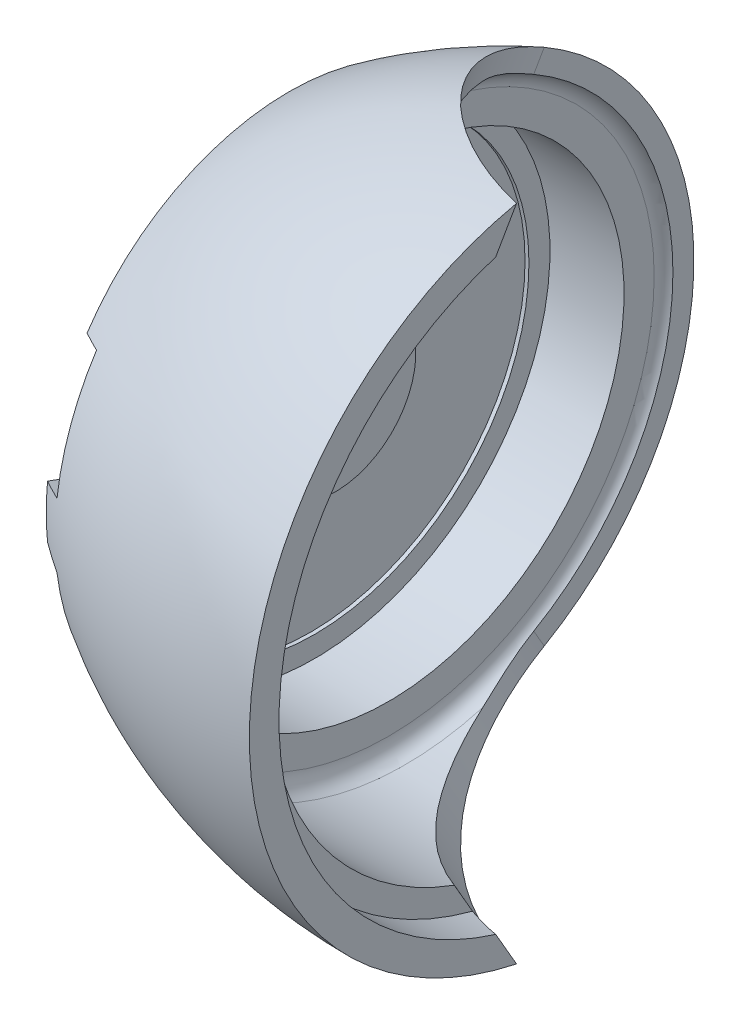
SolidWorks part; units mm, degrees
ref_plane "Front Plane" through (0, 0, 0) normal (0, 0, 1) x (1, 0, 0)
ref_plane "Top Plane" through (0, 0, 0) normal (0, 1, 0) x (1, 0, 0)
ref_plane "Right Plane" through (0, 0, 0) normal (1, 0, 0) x (0, 0, -1)
sketch "Sketch1" plane through (0, 0, 0) normal (0, 0, 1) x (1, 0, 0)
  line L0 (0, -55) -> (0, 55) construction
  line L1 (55, 0) -> (-55, 0) construction
  line L3 (-39.088, 0) -> (-39.088, 12.4)
  line L4 (-39.088, 12.4) -> (-42.39, 12.4)
  line L5 (-42.3, 33.02) -> (-42.3, 36.2585)
  line L7 (-42.988, 0) -> (-39.088, 0)
  line L9 (-30.9, 36.2585) -> (-42.3, 36.2585)
  line L10 (-46.2, 37.409) -> (-46.2, 8.59)
  line L14 (-30.9, 43.434) -> (-5.91, 43.434)
  line L17 (-46.2, 8.59) -> (-42.988, 8.59)
  line L18 (-42.988, 8.59) -> (-42.988, 0)
  line L19 (-42.3, 33.02) -> (-42.9, 33.02)
  line L20 (-42.9, 33.02) -> (-42.9, 12.4)
  line L21 (-42.9, 12.4) -> (-42.39, 12.4)
  line L22 (-30.9, 36.2585) -> (-30.9, 43.434)
  line L23 (-0.51, 51.8144) -> (-0.51, 47.244)
  line L24 (-0.51, 47.244) -> (-5.91, 47.244)
  line L25 (-5.91, 47.244) -> (-5.91, 43.434)
  arc A1 (-0.51, 51.8144) -> (-46.2, 37.409) centre (0, -29.464) ccw
  dimension "D1" = 81.28
  dimension "D2" = 43.434
  dimension "D3" = 46.2
  dimension "D4" = 12.4
  dimension "D5" = 7.112
  dimension "D6" = 11.4
  dimension "D7" = 29.464
  dimension "D8" = 3.9
  dimension "D9" = 36.2585
  dimension "D10" = 5.4
  dimension "D11" = 0.51
  dimension "D12" = 3.9
  dimension "D13" = 3.81
  dimension "D14" = 0.6
  dimension "D15" = 33.02
  dimension "D16" = 3.81
revolve "Revolve1" add sketch "Sketch1" angle 360 about L7
fillet "Fillet1" radius 2.54 1 edges at (-30.9, 0, 43.434)
ref_axis "Axis1" through (-48.7934, 0, 0) along (1, 0, 0)
ref_plane "Plane3" through (0, 0, 0) normal (0, -0.866, 0.5) x (1, 0, 0)
sketch "Sketch9" plane through (0, 0, 0) normal (0, -0.866, 0.5) x (1, 0, 0)
  line L0 (-48.7934, 0) -> (18.8214, 0) construction
  line L2 (0, -53.5869) -> (0, 53.5869) construction
  circle A0 centre (5.08, 0) radius 35.052
  dimension "D1" = 70.104
  dimension "D2" = 5.08
extrude "Cut-Extrude4" cut sketch "Sketch9" against normal blind 57.912
mirror "Mirror3" about plane through (0, 0, 0) normal (0, 1, 0) of "Cut-Extrude4"
ref_plane "Plane4" through (0, 0, 0) normal (0, -0.5, -0.866) x (1, 0, 0)
sketch "Sketch10" plane through (0, 0, 0) normal (0, -0.5, -0.866) x (1, 0, 0)
  line L1 (-29.972, -27.8884) -> (28.0432, -27.8884)
  line L2 (-29.972, -27.8884) -> (-29.972, -56.7179)
  line L3 (-29.972, -56.7179) -> (28.0432, -56.7179)
  line L4 (28.0432, -27.8884) -> (28.0432, -56.7179)
  line L5 (-29.972, -42.8569) -> (-29.972, -46.0881) construction
revolve "Cut-Revolve2" cut sketch "Sketch10" angle 120 about axis through (-48.7934, 0, 0) along (1, 0, 0)
ref_plane "Plane5" through (0, 0, 0) normal (0, -0.342, -0.9397) x (1, 0, 0)
sketch "Sketch11" plane through (0, 0, 0) normal (0, -0.342, -0.9397) x (1, 0, 0)
  line L1 (-42.3, 8.89) -> (-47.38, 8.89)
  line L2 (-42.3, 8.89) -> (-42.3, -8.89)
  line L3 (-42.3, -8.89) -> (-47.38, -8.89)
  line L4 (-47.38, 8.89) -> (-47.38, -8.89)
  line L5 (-48.7934, 0) -> (18.8214, 0) construction
  line L6 (-42.3, -36.2585) -> (-42.3, 36.2585) construction
  point P6 (-42.3, 0)
  dimension "D1" = 5.08
  dimension "D2" = 17.78
extrude "Cut-Extrude5" cut sketch "Sketch11" against normal blind 31.75 from offset 31.75 offset against normal yes
fillet "Fillet2" radius 2.54 1 edges at (-42.9, 10.8591, 29.8352)
mirror "Mirror4" about plane through (0, 0, 0) normal (0, 1, 0) of "Cut-Extrude5"
